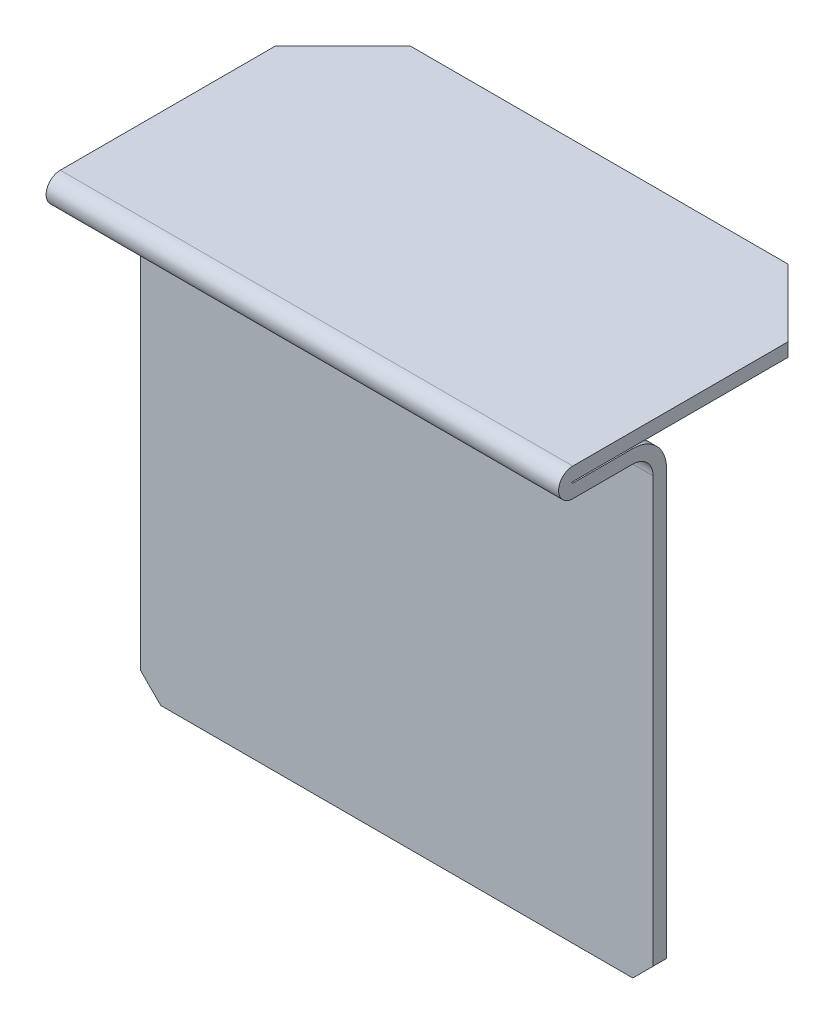
SolidWorks part; units mm, degrees
ref_plane "Front" through (0, 0, 0) normal (0, 0, 1) x (1, 0, 0)
ref_plane "Top" through (0, 0, 0) normal (0, 1, 0) x (1, 0, 0)
ref_plane "Right" through (0, 0, 0) normal (1, 0, 0) x (0, 0, -1)
sketch "Sketch1" plane through (0, 0, 0) normal (1, 0, 0) x (0, 0, -1)
  line L0 (0, 0) -> (0, 33)
  line L1 (-1.5, 34.5) -> (-5.95, 34.5)
  line L2 (-5.95, 36.6) -> (15, 36.6)
  line L3 (1, 0) -> (1, 33)
  line L4 (-1.5, 35.5) -> (-5.95, 35.5)
  line L5 (-5.95, 35.6) -> (15, 35.6)
  line L6 (-5.95, 35.6) -> (289.4293, 35.6) construction
  line L7 (-5.95, 36.6) -> (289.4293, 36.6) construction
  line L8 (15, 36.6) -> (15, 35.6)
  line L9 (0, 0) -> (1, 0)
  line L10 (0, 0) -> (0, 34.5) construction
  line L11 (0, 34.5) -> (-5.95, 34.5) construction
  line L12 (1, 0) -> (1, 35.5) construction
  line L13 (1, 35.5) -> (-5.95, 35.5) construction
  arc A0 (-5.95, 34.5) -> (-5.95, 36.6) centre (-5.95, 35.55) cw
  arc A1 (-5.95, 35.5) -> (-5.95, 35.6) centre (-5.95, 35.55) cw
  arc A2 (0, 33) -> (-1.5, 34.5) centre (-1.5, 33) ccw
  arc A3 (1, 33) -> (-1.5, 35.5) centre (-1.5, 33) ccw
  point P13 (-7, 35.55)
  dimension "D6" = 1.5
  dimension "D2" = 2.1
  dimension "D3" = 36.6
  dimension "D4" = 7
  dimension "D5" = 22
  dimension "D1" = 1
extrude "Boss-Extrude1" add sketch "Sketch1" along normal blind 38
chamfer "Chamfer1" distance 5 angle 45 2 edges at (0, 36.1, -15) (38, 36.1, -15)
chamfer "Chamfer2" distance 1.5 angle 45 2 edges at (0, 0, -0.5) (38, 0, -0.5)
sheet metal parameters "Sheet-Metal2" [suppressed] parameters "D1"=30
bend "RoundBend1" [suppressed] bend radius 1.5 bend angle 90 parameters "D5"=1
flatten bends "Flatten-Bends1" [suppressed] parameters "D1"=0
sketch "Sharp-Sketch1" [suppressed] plane through (0, 0, 0) normal (0, 0, 1) x (1, 0, 0)
  line L0 (38, 34.5708) -> (0, 34.5708) construction
  line L1 (0, 41.4555) -> (38, 41.4555) construction
bend "RoundBend2" [suppressed] bend radius 0.05 bend angle 180 parameters "D5"=2
process bends "Process-Bends1" [suppressed] parameters "D1"=0
sketch "Flat-Sketch1" [suppressed] plane through (0, 0, 0) normal (0, 0, 1) x (1, 0, 0)
sketch "Sketch8" [suppressed] plane through (0, 0, 0) normal (0, 0, 1) x (1, 0, 0)
  line L0 (0, 22) -> (38, 22)
  line L1 (0, 33) -> (0, 1.5) construction
  line L2 (38, 33) -> (38, 1.5) construction
  line L3 (36.5, 0) -> (1.5, 0) construction
  dimension "D1" = 22
sketched bend "Sketched Bend1" [suppressed] parameters "D1"=30
bend "SketchBend1" [suppressed] bend radius 30 bend angle 25 parameters "D5"=3
flat pattern "Flat-Pattern2" [suppressed]
sketch "Bend-Lines2" [suppressed] plane through (0, 0, 0) normal (0, 0, 1) x (1, 0, 0)
  line L0 (0, 41.4555) -> (38, 41.4555) construction
  line L1 (0, 34.5708) -> (38, 34.5708) construction
  line L2 (0, 41.4555) -> (38, 41.4555) construction
  line L3 (0, 34.5708) -> (38, 34.5708) construction
sketch3d "Bounding-Box2" [suppressed]
  line L0 (0, 63.2695, 0) -> (0, 0, 0) construction
  line L1 (-38, 63.2695, 0) -> (-38, 0, 0) construction
  line L2 (0, 63.2695, 0) -> (-38, 63.2695, 0) construction
  line L3 (0, 0, 0) -> (-38, 0, 0) construction
bend of the flat pattern "Flatten-<RoundBend1>1" [suppressed]
bend of the flat pattern "Flatten-<RoundBend2>1" [suppressed]
bend of the flat pattern "Flatten-<SketchBend1>1" [suppressed]
